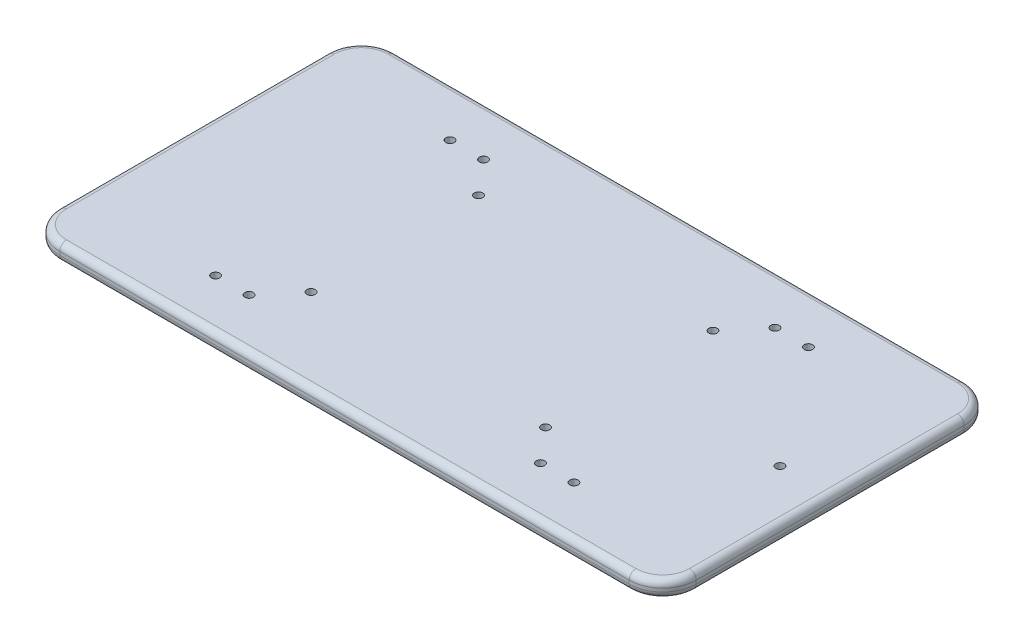
SolidWorks part; units mm, degrees
ref_plane "Front Plane" through (0, 0, 0) normal (0, 0, 1) x (1, 0, 0)
ref_plane "Top Plane" through (0, 0, 0) normal (0, 1, 0) x (1, 0, 0)
ref_plane "Right Plane" through (0, 0, 0) normal (1, 0, 0) x (0, 0, -1)
sketch "Sketch1" plane through (0, 0, 0) normal (0, 1, 0) x (1, 0, 0)
  line L0 (80, 50) -> (80, -50) construction
  line L1 (-95, -50) -> (95, -50)
  line L2 (-95, -50) -> (-95, 50)
  line L3 (-95, 50) -> (95, 50)
  line L4 (95, -50) -> (95, 50)
  line L5 (-95, -50) -> (95, 50) construction
  line L6 (-95, 50) -> (95, -50) construction
  line L7 (-35, -25) -> (35, -25) construction
  line L8 (-35, -25) -> (-35, 25) construction
  line L9 (-35, 25) -> (35, 25) construction
  line L10 (35, -25) -> (35, 25) construction
  line L11 (-35, -25) -> (35, 25) construction
  line L12 (-35, 25) -> (35, -25) construction
  line L13 (0, 0) -> (23.6983, 0) construction
  line L14 (0, 0) -> (0, 16.3475) construction
  circle A0 centre (-35, 25) radius 1.25
  circle A1 centre (35, 25) radius 1.25
  circle A2 centre (35, -25) radius 1.25
  circle A3 centre (-35, -25) radius 1.25
  circle A4 centre (80, 0) radius 1.25
  circle A5 centre (-53.5, -35) radius 1.25
  circle A6 centre (-43.5, -35) radius 1.25
  circle A7 centre (-43.5, 35) radius 1.25
  circle A8 centre (-53.5, 35) radius 1.25
  circle A9 centre (43.5, 35) radius 1.25
  circle A10 centre (53.5, 35) radius 1.25
  circle A11 centre (53.5, -35) radius 1.25
  circle A12 centre (43.5, -35) radius 1.25
  point P0 (0, 0)
  point P6 (0, 0)
  dimension "D5" = 2.5
  dimension "D7" = 2.5
  dimension "D8" = 2.5
  dimension "D9" = 10
  dimension "D1" = 190
  dimension "D2" = 100
  dimension "D3" = 70
  dimension "D4" = 50
  dimension "D6" = 15
  dimension "D10" = 43.5
  dimension "D11" = 15
extrude "Boss-Extrude1" add sketch "Sketch1" along normal blind 5
fillet "Fillet1" radius 10 4 edges at (95, 2.5, 50) (95, 2.5, -50) (-95, 2.5, -50) (-95, 2.5, 50)
fillet "Fillet2" radius 2 16 edges at (-92.0711, 0, 47.0711) (-95, 0, 0) (-92.0711, 0, -47.0711) (0, 0, -50) (92.0711, 0, -47.0711) (95, 0, 0) (92.0711, 0, 47.0711) (-92.0711, 5, 47.0711) (-95, 5, 0) (-92.0711, 5, -47.0711) (0, 5, -50) (92.0711, 5, -47.0711) (95, 5, 0) (92.0711, 5, 47.0711) (0, 0, 50) (0, 5, 50)
scale "Scale1" scale about centroid uniform scaling yes scale factor 18
